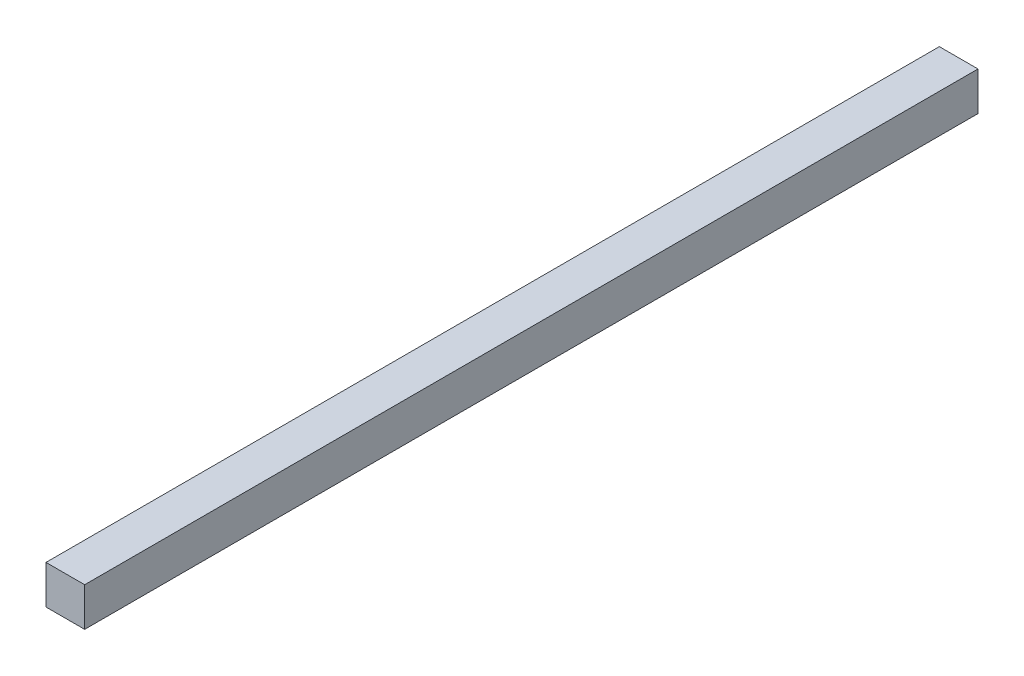
SolidWorks part; units mm, degrees
ref_plane "Plan de face" through (0, 0, 0) normal (0, 0, 1) x (1, 0, 0)
ref_plane "Plan de dessus" through (0, 0, 0) normal (0, 1, 0) x (1, 0, 0)
ref_plane "Plan de droite" through (0, 0, 0) normal (1, 0, 0) x (0, 0, -1)
sketch "Esquisse1" plane through (0, 0, 0) normal (0, 0, 1) x (1, 0, 0)
  line L1 (0, 0) -> (10, 0)
  line L2 (0, 0) -> (0, 10)
  line L3 (0, 10) -> (10, 10)
  line L4 (10, 0) -> (10, 10)
  dimension "D1" = 10
  dimension "D2" = 10
extrude "Boss.-Extru.1" add sketch "Esquisse1" along normal blind 231
